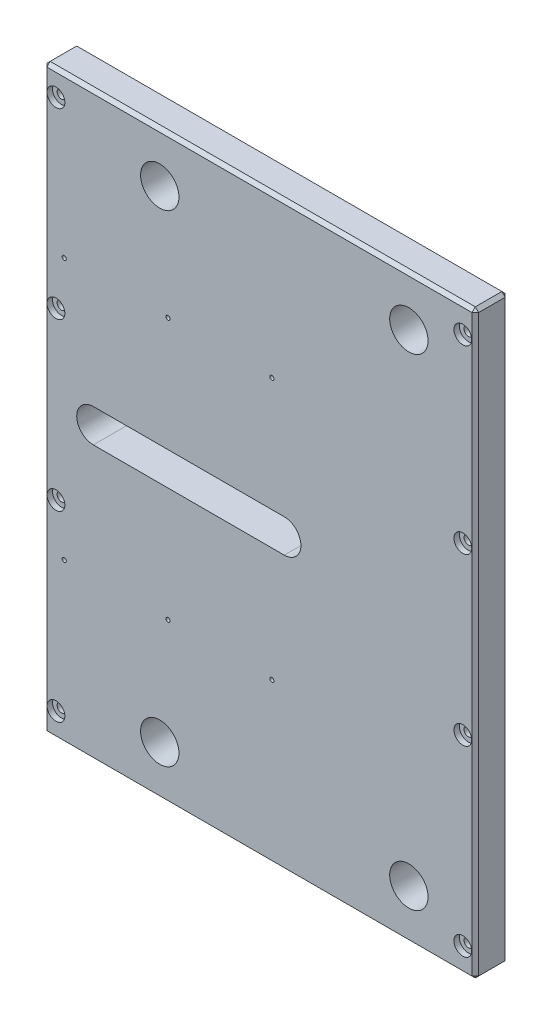
SolidWorks part; units mm, degrees
ref_plane "前视基准面" through (0, 0, 0) normal (0, 0, 1) x (1, 0, 0)
ref_plane "上视基准面" through (0, 0, 0) normal (0, 1, 0) x (1, 0, 0)
ref_plane "右视基准面" through (0, 0, 0) normal (1, 0, 0) x (0, 0, -1)
sketch "草图1" plane through (0, 0, 0) normal (0, 0, 1) x (1, 0, 0)
  line L1 (0, 0) -> (520, 0)
  line L2 (0, 0) -> (0, 700)
  line L3 (0, 700) -> (520, 700)
  line L4 (520, 0) -> (520, 700)
  dimension "D1" = 700
  dimension "D2" = 520
extrude "凸台-拉伸1" add sketch "草图1" along normal blind 40
sketch "草图2" plane through (0, 0, 40) normal (0, 0, 1) x (1, 0, 0)
  line L0 (0, 700) -> (0, 0) construction
  line L1 (520, 700) -> (0, 700) construction
  line L2 (520, 0) -> (520, 700) construction
  line L3 (0, 0) -> (520, 0) construction
  circle A0 centre (140, 60) radius 23.1
  circle A1 centre (440, 60) radius 23.1
  circle A2 centre (440, 640) radius 23.1
  circle A3 centre (140, 640) radius 23.1
  dimension "D1" = 46.2
  dimension "D2" = 46.2
  dimension "D3" = 46.2
  dimension "D4" = 46.2
  dimension "D5" = 140
  dimension "D6" = 60
  dimension "D7" = 60
  dimension "D8" = 80
  dimension "D9" = 80
  dimension "D10" = 60
  dimension "D11" = 60
  dimension "D12" = 140
extrude "切除-拉伸1" cut sketch "草图2" against normal through all
chamfer "倒角1" distance 4 angle 45 12 edges at (0, 350, 40) (0, 350, 0) (260, 700, 40) (0, 700, 20) (260, 700, 0) (520, 350, 40) (520, 700, 20) (520, 350, 0) (0, 0, 20) (260, 0, 40) (520, 0, 20) (260, 0, 0)
hole_wizard "M6x1.0 螺纹孔1" positions "草图4" profile "草图3" tap size "M6x1.0" standard "Ansi Metric" end condition through all
sketch "草图4" plane through (0, 0, 40) normal (0, 0, 1) x (1, 0, 0)
  point P0 (25, 507.5)
  point P3 (150, 507.5)
  point P6 (275, 507.5)
  point P9 (275, 192.5)
  point P12 (150, 192.5)
  point P15 (25, 192.5)
sketch "草图3" plane through (25, 507.5, 40) normal (1, 0, 0) x (0, -1, 0)
  line L0 (0, 0) -> (0, 40)
  line L1 (0, 40) -> (2.5, 40)
  line L2 (2.5, 40) -> (2.5, 0)
  line L5 (2.5, 0) -> (0, 0)
  line L11 (0, -6.35) -> (0, 107.95) construction
  dimension "Í¨¿×ÂÝÎÆ¿××êÍ·Ö±¾¶" = 5
  dimension "Í¨¿×ÂÝÎÆ¿××êÍ·Éî¶È" = 40
cosmetic thread "孔螺蚊线1" parameters "D2"=6
cosmetic thread "孔螺蚊线2" parameters "D2"=6
cosmetic thread "孔螺蚊线3" parameters "D2"=6
cosmetic thread "孔螺蚊线4" parameters "D2"=6
cosmetic thread "孔螺蚊线5" parameters "D2"=6
cosmetic thread "孔螺蚊线6" parameters "D2"=6
sketch "草图5" plane through (0, 0, 40) normal (0, 0, 1) x (1, 0, 0)
  line L0 (60, 350) -> (290, 350) construction
  line L1 (60, 370) -> (290, 370)
  line L2 (60, 330) -> (290, 330)
  line L3 (4, 696) -> (4, 4) construction
  line L4 (4, 700) -> (516, 700) construction
  arc A0 (60, 370) -> (60, 330) centre (60, 350) ccw
  arc A1 (290, 330) -> (290, 370) centre (290, 350) ccw
  point P4 (175, 350)
  dimension "D1" = 20
  dimension "D3" = 56
  dimension "D4" = 350
  dimension "D2" = 230
extrude "切除-拉伸2" cut sketch "草图5" against normal through all
hole_wizard "M10 六角头螺钉的柱形沉头孔1" positions "草图7" profile "草图6" counterbore size "M10" standard "Ansi Metric" end condition through all
sketch "草图7" plane through (0, 0, 40) normal (0, 0, 1) x (1, 0, 0)
  line L0 (0, 4) -> (0, 696) construction
  line L1 (4, 700) -> (516, 700) construction
  line L2 (516, 0) -> (4, 0) construction
  line L5 (520, 696) -> (520, 4) construction
  point P0 (15, 670)
  point P2 (15, 450)
  point P4 (15, 250)
  point P6 (15, 30)
  point P8 (505, 30)
  point P10 (505, 250)
  point P12 (505, 450)
  point P14 (505, 667.6229)
  dimension "D1" = 15
  dimension "D2" = 30
  dimension "D3" = 250
  dimension "D4" = 15
  dimension "D5" = 250
  dimension "D6" = 15
  dimension "D7" = 30
  dimension "D8" = 15
  dimension "D9" = 15
  dimension "D10" = 250
  dimension "D11" = 15
  dimension "D12" = 250
  dimension "D13" = 30
  dimension "D14" = 15
  dimension "D15" = 15
sketch "草图6" plane through (15, 670, 40) normal (1, 0, 0) x (0, -1, 0)
  line L0 (0, 0) -> (0, 40)
  line L1 (0, 40) -> (5.25, 40)
  line L3 (5.25, 40) -> (5.25, 6.63)
  line L4 (5.25, 6.63) -> (10.74, 6.63)
  line L5 (10.74, 6.63) -> (10.74, 0)
  line L7 (10.74, 0) -> (0, 0)
  line L11 (0, -6.35) -> (0, 107.95) construction
  dimension "通孔孔直径" = 10.5
  dimension "通孔孔深度" = 40
  dimension "柱形沉头孔直径" = 21.48
  dimension "柱形沉头孔深度" = 6.63
hole_wizard "M6 螺纹孔1" positions "草图9" profile "草图8" tap size "M6" standard "Gb"
sketch "草图9" plane through (0, 0, 0) normal (0, -1, 0) x (-1, 0, 0)
  line L0 (-260, 29.03) -> (-260, -156.1614) construction
  line L2 (-516, 0) -> (-4, 0) construction
  point P0 (-260, -20)
  dimension "D1" = 0
  dimension "D2" = 20
sketch "草图8" plane through (260, 0, 20) normal (1, 0, 0) x (0, 0, -1)
  line L0 (0, 0) -> (0, 16.5022)
  line L1 (0, 16.5022) -> (2.5, 15)
  line L2 (2.5, 15) -> (2.5, 0)
  line L5 (2.5, 0) -> (0, 0)
  line L10 (0, 16.5022) -> (-2.5, 15) construction
  line L11 (0, -6.35) -> (0, 107.95) construction
  dimension "螺纹孔钻头直径" = 5
  dimension "螺纹孔钻头深度" = 15
  dimension "导头角度" = 118
cosmetic thread "孔螺蚊线7" parameters "D1"=12, "D2"=6
